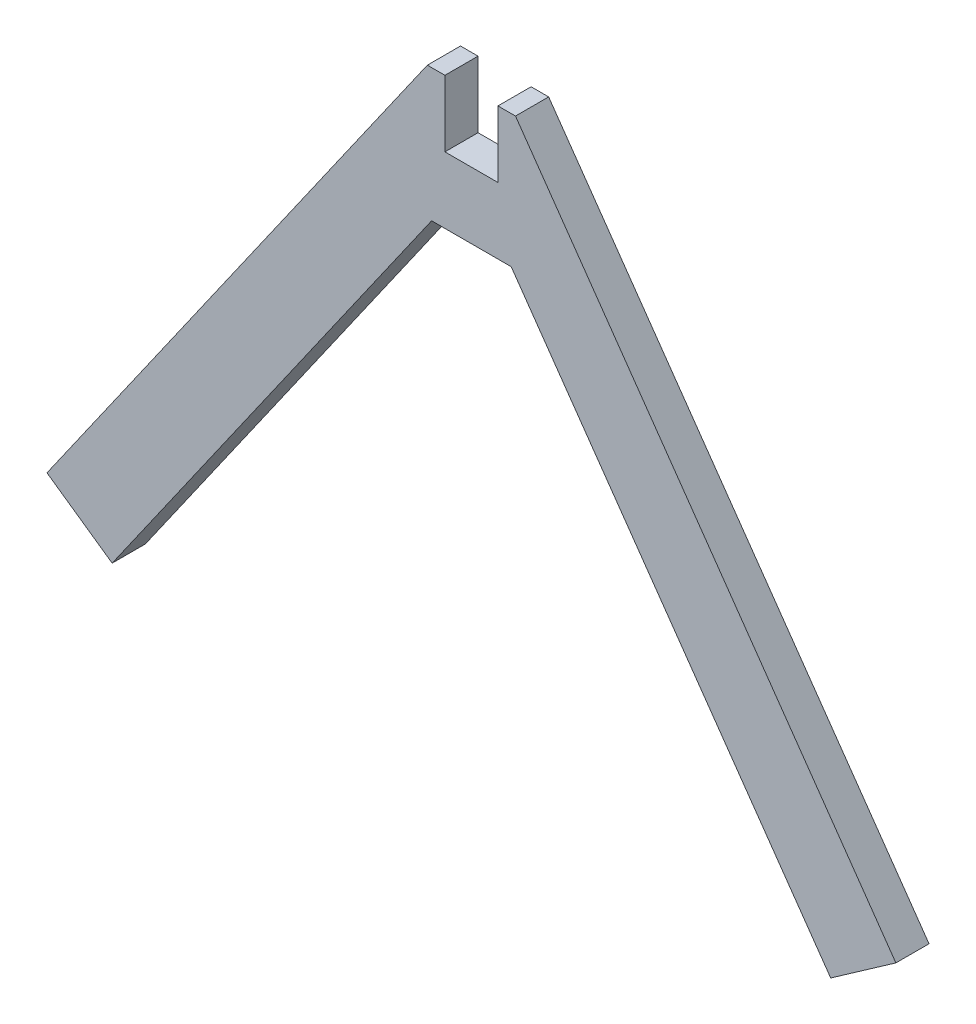
SolidWorks part; units mm, degrees
material "Balsa"
ref_plane "Front Plane" through (0, 0, 0) normal (0, 0, 1) x (1, 0, 0)
ref_plane "Top Plane" through (0, 0, 0) normal (0, 1, 0) x (1, 0, 0)
ref_plane "Right Plane" through (0, 0, 0) normal (1, 0, 0) x (0, 0, -1)
sketch "Sketch1" plane through (0, 0, 0) normal (0, 0, 1) x (1, 0, 0)
  line L2 (0, 49.4643) -> (0, -61.7029) construction
  line L3 (-16.5003, 0) -> (93.5326, 0) construction
  line L4 (4.2197, 0) -> (-4.2197, 0)
  line L5 (-4.2197, 0) -> (-40.6418, -52.0162)
  line L6 (-40.6418, -52.0162) -> (-34.3998, -56.3868)
  line L7 (-34.3998, -56.3868) -> (-3.81, -12.7)
  line L8 (-3.81, -12.7) -> (3.81, -12.7)
  line L9 (34.3998, -56.3868) -> (3.81, -12.7)
  line L10 (40.6418, -52.0162) -> (34.3998, -56.3868)
  line L11 (4.2197, 0) -> (40.6418, -52.0162)
  point P0 (0, 0)
  point P16 (0, 0)
  point P17 (0, -12.7)
  dimension "D1" = 12.7
  dimension "D2" = 7.62
  dimension "D3" = 55
  dimension "D4" = 63.5
  dimension "D5" = 3.81
extrude "Boss-Extrude1" add sketch "Sketch1" along normal blind 3.175
sketch "Sketch2" plane through (0, 0, 3.175) normal (0, 0, 1) x (1, 0, 0)
  line L0 (0, 0) -> (0, -12.7) construction
  line L1 (4.2197, 0) -> (-4.2197, 0) construction
  line L2 (-3.81, -12.7) -> (3.81, -12.7) construction
  line L3 (2.54, 0) -> (-2.54, 0)
  line L4 (-2.54, 0) -> (-2.54, -6.35)
  line L5 (-2.54, -6.35) -> (2.54, -6.35)
  line L6 (2.54, 0) -> (2.54, -6.35)
  point P10 (0, -6.35)
  dimension "D1" = 2.54
  dimension "D2" = 6.35
extrude "Cut-Extrude1" cut sketch "Sketch2" against normal up to next
